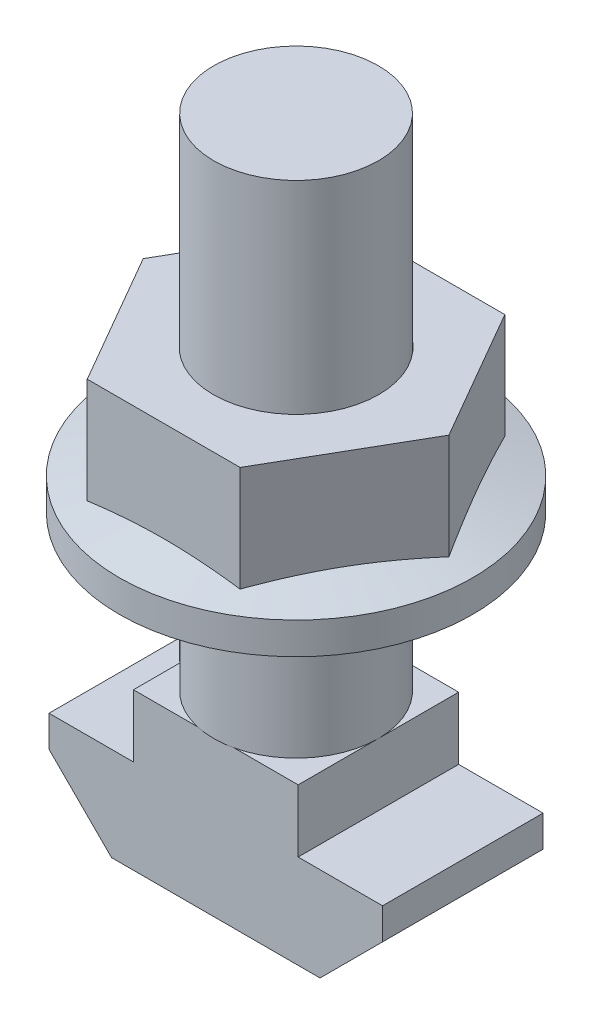
SolidWorks part; units mm, degrees
ref_plane "Front Plane" through (0, 0, 0) normal (0, 0, 1) x (1, 0, 0)
ref_plane "Top Plane" through (0, 0, 0) normal (0, 1, 0) x (1, 0, 0)
ref_plane "Right Plane" through (0, 0, 0) normal (1, 0, 0) x (0, 0, -1)
sketch "Sketch0" plane through (0, 0, 0) normal (0, 0, 1) x (1, 0, 0)
  line L0 (0, 24) -> (0, 0) construction
  line L1 (-3.95, 0) -> (3.95, 0) construction
  line L2 (-3.95, 0) -> (-3.95, -3) construction
  line L3 (-3.95, -3) -> (-8, -3) construction
  line L4 (-8, -3) -> (-8, -4.5) construction
  line L5 (-8, -4.5) -> (-5, -7.5) construction
  line L6 (-5, -7.5) -> (5, -7.5) construction
  line L7 (0, 0) -> (0, -7.5) construction
  line L8 (8, -4.5) -> (5, -7.5) construction
  line L9 (8, -3) -> (8, -4.5) construction
  line L10 (3.95, -3) -> (8, -3) construction
  line L11 (3.95, 0) -> (3.95, -3) construction
  dimension "D1" = 24
  dimension "D8" = 7.9
  dimension "D2" = 27
  dimension "D3" = 4.5
  dimension "D4" = 16
  dimension "D5" = 45
  dimension "D6" = 3
  dimension "D7" = 3
sketch "Sketch1" plane through (0, 0, 0) normal (0, 1, 0) x (1, 0, 0)
  circle A0 centre (0, 0) radius 3.95
  point P2 (3.95, 0)
  point P3 (-3.95, 0)
  dimension "D1" = 7.9
extrude "Boss-Extrude1" add sketch "Sketch1" along normal up to vertex (24 mm away) from vertex at 0 up to point (0, 24, 0) starting at point (0, 0, 0)
sketch "Sketch2" plane through (0, 24, 0) normal (0, 1, 0) x (-1, 0, 0)
  circle A2 centre (0, 0) radius 3.9688
  point P0 (0, -3.9688)
  dimension "D1" = 7.9375
sketch "Sketch3" plane through (0, 0, 0) normal (1, 0, 0) x (0, 0, -1)
  line L0 (4.1215, 23.9118) -> (2.8994, 24.6174) construction
  line L1 (2.8994, 24.6174) -> (4.1215, 25.3229) construction
  line L2 (4.1215, 25.3229) -> (4.1215, 23.9118) construction
  line L3 (3.0522, 24.5292) -> (3.0522, 24.7056) construction
  line L4 (3.9688, 24) -> (3.9688, 25.2347) construction
  line L5 (2.8994, 24.6174) -> (3.0522, 24.6174) construction
  line L6 (3.9688, 24.6174) -> (4.1215, 24.6174) construction
  line L8 (2.8994, 24.6174) -> (-3.95, 24.6174) construction
  line L9 (3.0522, 24.5292) -> (4.0451, 23.9559)
  line L10 (3.0522, 24.5292) -> (3.0522, 24.7056)
  line L11 (3.0522, 24.7056) -> (4.0451, 25.2788)
  line L12 (4.0451, 25.2788) -> (4.0451, 23.9559)
  line L13 (-3.95, 24) -> (-3.95, 0) construction
  line L14 (-3.95, 24.6174) -> (-3.95, 23.2063) construction
  line L15 (-3.95, 23.2063) -> (-3.95, 21.7951) construction
  line L16 (-3.95, 21.7951) -> (-3.95, 20.384) construction
  line L17 (-3.95, 20.384) -> (-3.95, 18.9729) construction
  point P15 (4.0451, 24.6174)
  dimension "D1" = 1.4111
  dimension "D2" = 0.1764
sketch "SketchZ" plane through (0, 0, 0) normal (0, 0, 1) x (1, 0, 0)
  line L0 (0, 23.2063) -> (0, 23.9118) construction
  line L1 (0, 23.559) -> (3.95, 23.559) construction
  line L2 (3.95, 23.559) -> (3.95, 22.1479) construction
  line L3 (0, 24.6174) -> (0, 23.2063) construction
sketch "Sketch5" plane through (0, 0, 0) normal (0, 0, 1) x (1, 0, 0)
  line L0 (-3.95, 0) -> (3.95, 0) construction
  line L1 (-3.95, 0) -> (-3.95, -3) construction
  line L2 (-3.95, -3) -> (-8, -3) construction
  line L3 (-8, -3) -> (-8, -4.5) construction
  line L4 (-8, -4.5) -> (-5, -7.5) construction
  line L5 (-5, -7.5) -> (5, -7.5) construction
  line L6 (8, -4.5) -> (5, -7.5) construction
  line L7 (8, -3) -> (8, -4.5) construction
  line L8 (3.95, -3) -> (8, -3) construction
  line L9 (3.95, 0) -> (3.95, -3) construction
  line L10 (-3.95, 0) -> (3.95, 0)
  line L11 (-3.95, 0) -> (-3.95, -3)
  line L12 (-3.95, -3) -> (-8, -3)
  line L13 (-8, -3) -> (-8, -4.5)
  line L14 (-8, -4.5) -> (-5, -7.5)
  line L15 (-5, -7.5) -> (5, -7.5)
  line L16 (8, -4.5) -> (5, -7.5)
  line L17 (8, -3) -> (8, -4.5)
  line L18 (3.95, -3) -> (8, -3)
  line L19 (3.95, 0) -> (3.95, -3)
extrude "Boss-Extrude2" add sketch "Sketch5" along normal mid plane 7.7
sketch "Sketch8" plane through (0, 0, 0) normal (0, 1, 0) x (1, 0, 0)
  line L0 (-5, 0) -> (5, 0) construction
  line L1 (7.3323, 0) -> (3.6662, 6.35)
  line L2 (3.6662, 6.35) -> (-3.6662, 6.35)
  line L3 (-3.6662, 6.35) -> (-7.3323, 0)
  line L4 (-7.3323, 0) -> (-3.6662, -6.35)
  line L5 (-3.6662, -6.35) -> (3.6662, -6.35)
  line L6 (3.6662, -6.35) -> (7.3323, 0)
  circle A0 centre (0, 0) radius 6.35 construction
  circle A2 centre (0, 0) radius 3.9688
  circle A3 centre (0, 0) radius 3.9688
  dimension "D1" = 12.7
  dimension "D2" = 0
extrude "Boss-Extrude3" add sketch "Sketch8" along normal blind 6.8834 from offset 7.41 separate body
sketch "Sketch10" plane through (0, 0, 0) normal (0, 0, 1) x (1, 0, 0)
  line L0 (-3.6662, 7.41) -> (-8.4709, 7.41)
  line L1 (-8.4709, 7.41) -> (-8.4709, 8.934)
  line L2 (0, 24) -> (0, 0) construction
  line L3 (-3.95, 0) -> (3.95, 0) construction
  line L4 (-3.6662, 7.41) -> (-3.6662, 10.2214)
  line L5 (-8.4709, 8.934) -> (-3.6662, 10.2214)
  line L6 (-0.8832, 0) -> (-3.95, 0) construction
  point P11 (-0.9994, -12.8132)
  dimension "D1" = 16.9418
  dimension "D2" = 1.524
  dimension "D3" = 75
  dimension "D4" = 7.41
revolve "Revolve1" add sketch "Sketch10" angle 360 mid plane about L2
